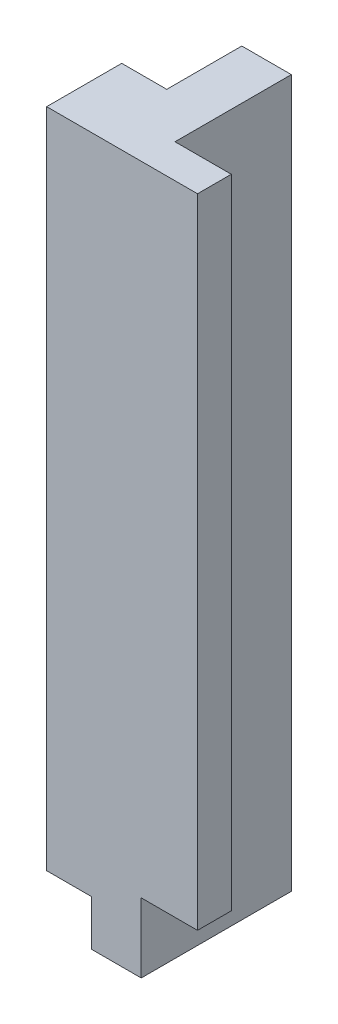
SolidWorks part; units mm, degrees
ref_plane "Front Plane" through (0, 0, 0) normal (0, 0, 1) x (1, 0, 0)
ref_plane "Top Plane" through (0, 0, 0) normal (0, 1, 0) x (1, 0, 0)
ref_plane "Right Plane" through (0, 0, 0) normal (1, 0, 0) x (0, 0, -1)
sketch "Sketch1" plane through (0, 0, 0) normal (0, 1, 0) x (1, 0, 0)
  line L1 (0, 0) -> (6.6, 0)
  line L2 (0, 0) -> (0, 20)
  line L3 (0, 20) -> (6.6, 20)
  line L4 (6.6, 0) -> (6.6, 20)
  dimension "D1" = 6.6
  dimension "D2" = 20
extrude "Boss-Extrude1" add sketch "Sketch1" along normal blind 94.25
sketch "Sketch3" plane through (0, 0, 0) normal (-1, 0, 0) x (0, 0, 1)
  line L0 (-20, 0) -> (0, 0) construction
  line L1 (0, 94.25) -> (-10, 94.25)
  line L2 (0, 94.25) -> (0, 6.08)
  line L3 (0, 6.08) -> (-10, 6.08)
  line L4 (-10, 94.25) -> (-10, 6.08)
  dimension "D1" = 6.08
  dimension "D2" = 10
extrude "Boss-Extrude2" add sketch "Sketch3" along normal blind 6
sketch "Sketch4" plane through (6.6, 0, 0) normal (1, 0, 0) x (0, 0, -1)
  line L1 (0, 94.25) -> (4.5, 94.25)
  line L2 (0, 94.25) -> (0, 9.25)
  line L3 (0, 9.25) -> (4.5, 9.25)
  line L4 (4.5, 94.25) -> (4.5, 9.25)
  dimension "D1" = 4.5
  dimension "D2" = 85
extrude "Boss-Extrude3" add sketch "Sketch4" along normal blind 7.5
